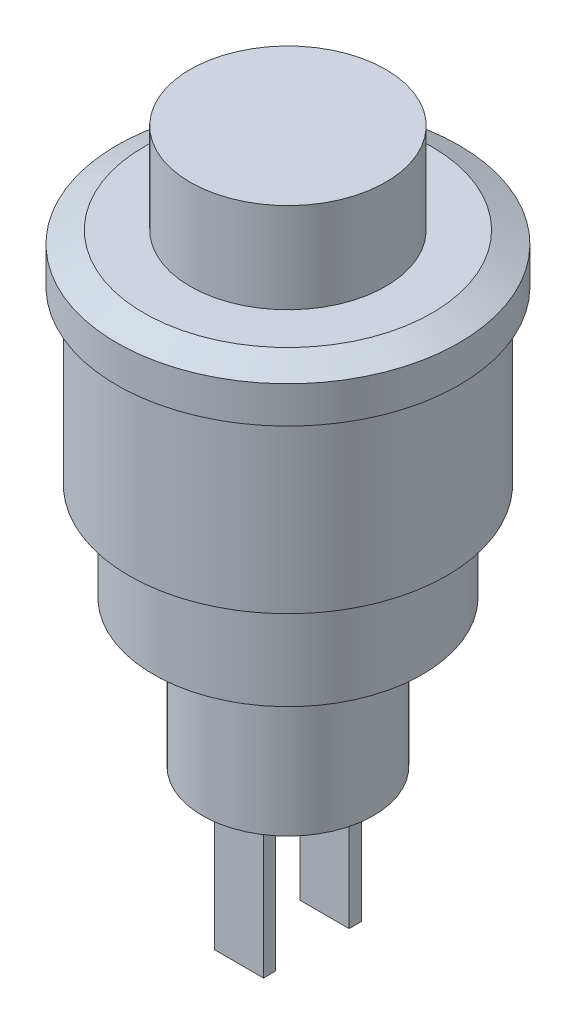
SolidWorks part; units mm, degrees
ref_plane "Plano frontal" through (0, 0, 0) normal (0, 0, 1) x (1, 0, 0)
ref_plane "Plano superior" through (0, 0, 0) normal (0, 1, 0) x (1, 0, 0)
ref_plane "Plano direito" through (0, 0, 0) normal (1, 0, 0) x (0, 0, -1)
sketch "Esboço1" plane through (0, 0, 0) normal (0, 0, 1) x (1, 0, 0)
  line L0 (0, 22.6898) -> (4, 22.6898)
  line L1 (4, 22.6898) -> (4, 19)
  line L2 (4, 19) -> (5.8913, 19)
  line L3 (5.8913, 19) -> (7, 18.5)
  line L4 (7, 18.5) -> (7, 17)
  line L5 (7, 17) -> (6.5, 17)
  line L6 (6.5, 17) -> (6.5, 10)
  line L7 (6.5, 10) -> (5.5, 10)
  line L8 (5.5, 10) -> (5.5, 6)
  line L9 (5.5, 6) -> (3.5, 6)
  line L10 (3.5, 6) -> (3.5, 0)
  line L11 (3.5, 0) -> (0, 0)
  line L12 (0, 0) -> (0, 22.6898)
  point P2 (0, 0)
  point P14 (9, 6)
  dimension "D1" = 4
  dimension "D2" = 6
  dimension "D3" = 7
  dimension "D4" = 1
  dimension "D5" = 2
  dimension "D6" = 3.5
  dimension "D7" = 4
  dimension "D8" = 7
  dimension "D9" = 2
  dimension "D10" = 1.5
revolve "Revolução1" add sketch "Esboço1" angle 360 about L12
sketch "Esboço2" plane through (0, 0, 0) normal (0, -1, 0) x (1, 0, 0)
  line L0 (1.4586, 0) -> (-1.2654, 0) construction
  line L1 (1, -1.5) -> (-1, -1.5)
  line L2 (1, -1.5) -> (1, -2)
  line L3 (1, -2) -> (-1, -2)
  line L4 (-1, -1.5) -> (-1, -2)
  line L5 (1, 2) -> (-1, 2)
  line L6 (-1, 1.5) -> (-1, 2)
  line L7 (1, 1.5) -> (-1, 1.5)
  line L8 (1, 1.5) -> (1, 2)
  point P4 (-1, -1.75)
  point P12 (0, -1.5)
  dimension "D1" = 0.5
  dimension "D2" = 2
  dimension "D3" = 2
extrude "Ressalto-extrusão1" add sketch "Esboço2" along normal blind 6
